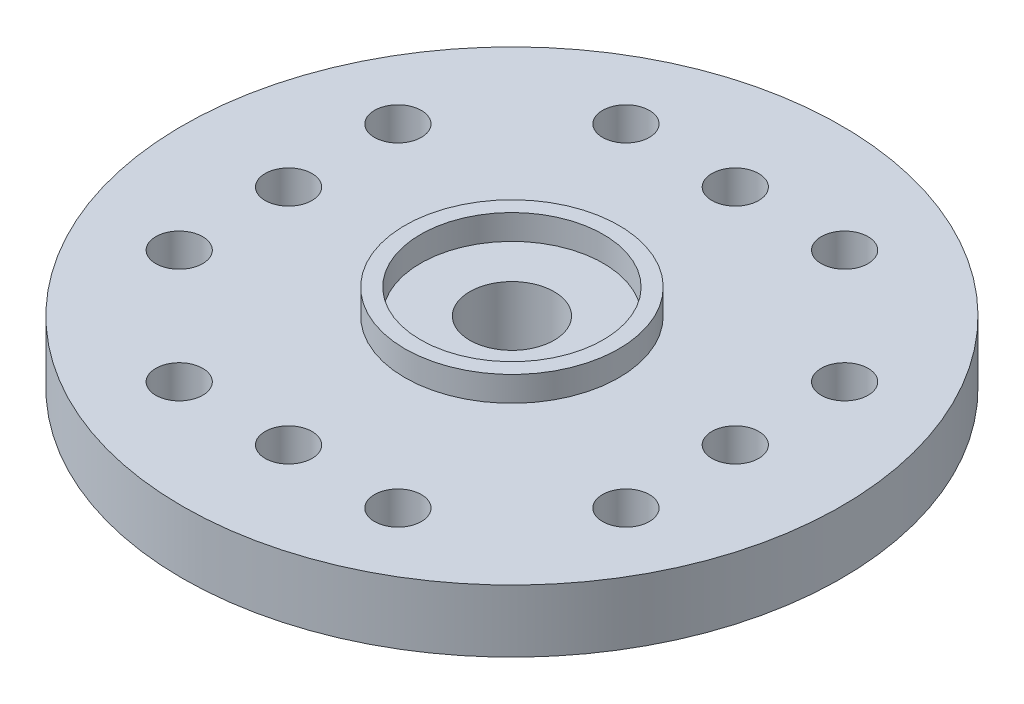
SolidWorks part; units mm, degrees
ref_plane "Front Plane" through (0, 0, 0) normal (0, 0, 1) x (1, 0, 0)
ref_plane "Top Plane" through (0, 0, 0) normal (0, 1, 0) x (1, 0, 0)
ref_plane "Right Plane" through (0, 0, 0) normal (1, 0, 0) x (0, 0, -1)
sketch "Sketch1" plane through (0, 0, 0) normal (0, 1, 0) x (1, 0, 0)
  circle A0 centre (0, 0) radius 4.35
  dimension "D1" = 8.7
extrude "Rebaixo de Encaixe" add sketch "Sketch1" along normal blind 2.6
sketch "Sketch14" plane through (0, 0, 0) normal (0, -1, 0) x (1, 0, 0)
  circle A0 centre (0, 0) radius 2.45
  dimension "D1" = 4.9
extrude "Furo de Encaixe - Servo" cut sketch "Sketch14" against normal blind 3
sketch "Sketch5" plane through (0, 2.6, 0) normal (0, 1, 0) x (1, 0, 0)
  circle A0 centre (0, 0) radius 1.35
  circle A1 centre (0, 0) radius 10.55
  dimension "D1" = 21.1
  dimension "D2" = 2.7
extrude "Base Redonda" add sketch "Sketch5" along normal blind 2
sketch "Sketch8" plane through (0, 4.6, 0) normal (0, 1, 0) x (1, 0, 0)
  circle A0 centre (0, 0) radius 3.425
  circle A1 centre (0, 0) radius 2.925
  dimension "D1" = 6.85
  dimension "D2" = 0.5
extrude "Ressalto" add sketch "Sketch8" along normal blind 0.8
sketch "Sketch9" plane through (0, 4.6, 0) normal (0, 1, 0) x (1, 0, 0)
  line L0 (0, 0) -> (0, 7.15) construction
  line L1 (-7.15, -7.15) -> (7.15, -7.15) construction
  line L2 (-7.15, -7.15) -> (-7.15, 7.15) construction
  line L3 (-7.15, 7.15) -> (7.15, 7.15) construction
  line L4 (7.15, -7.15) -> (7.15, 7.15) construction
  line L5 (-7.15, -7.15) -> (7.15, 7.15) construction
  line L6 (-7.15, 7.15) -> (7.15, -7.15) construction
  circle A0 centre (0, 7.15) radius 0.75
  circle A1 centre (3.5, 7.15) radius 0.75
  circle A2 centre (-3.5, 7.15) radius 0.75
  circle A3 centre (7.15, 3.5) radius 0.75
  circle A4 centre (7.15, 0) radius 0.75
  circle A5 centre (7.15, -3.5) radius 0.75
  circle A6 centre (3.5, -7.15) radius 0.75
  circle A7 centre (0, -7.15) radius 0.75
  circle A8 centre (-3.5, -7.15) radius 0.75
  circle A9 centre (-7.15, -3.5) radius 0.75
  circle A10 centre (-7.15, 0) radius 0.75
  circle A11 centre (-7.15, 3.5) radius 0.75
  point P0 (0, 0)
  point P6 (7.15, 0)
  point P35 (0, 0)
  dimension "D3" = 1.5
  dimension "D4" = 3.5
  dimension "D5" = 3.5
  dimension "D1" = 14.3
  dimension "D2" = 14.3
  dimension "D6" = 4
extrude "Furos de Fixação - Carga Redondo" cut sketch "Sketch9" against normal through all
sketch "Sketch10" [suppressed] plane through (0, 2.6, 0) normal (0, 1, 0) x (1, 0, 0)
  line L0 (0, 0) -> (25.65, 0) construction
  line L1 (26.1003, 3.8236) -> (0.8012, 6.803)
  line L2 (26.1003, -3.8236) -> (0.8012, -6.803)
  arc A0 (0.8012, 6.803) -> (0.8012, -6.803) centre (0, 0) ccw
  circle A1 centre (0, 0) radius 1.35
  arc A3 (26.1003, -3.8236) -> (26.1003, 3.8236) centre (25.65, 0) ccw
  dimension "D1" = 13.7
  dimension "D2" = 32.5
  dimension "D3" = 3.85
  dimension "D4" = 2.7
extrude "Base de 1 Braço" [suppressed] add sketch "Sketch10" along normal blind 4.3
sketch "Sketch11" [suppressed] plane through (0, 6.9, 0) normal (0, 1, 0) x (1, 0, 0)
  circle A0 centre (0, 0) radius 4.25
  dimension "D1" = 8.5
extrude "Rebaixo de Alojamento - 1 Braço" [suppressed] cut sketch "Sketch11" against normal blind 2.1 draft 25
sketch "Sketch12" [suppressed] plane through (0, 0, 0) normal (0, 0, 1) x (1, 0, 0)
  line L0 (29.5, 4.75) -> (11.5, 4.75) construction
  line L1 (29.5, 2.6) -> (29.5, 6.9) construction
  line L2 (11.5, 2.6) -> (11.5, 6.9) construction
  line L3 (0.8012, 2.6) -> (26.1003, 2.6) construction
  line L4 (0.8012, 6.9) -> (26.1003, 6.9) construction
  line L5 (29.5, 2.6) -> (29.5, 3.75)
  line L6 (29.5, 6.9) -> (11.5, 6.9)
  line L7 (29.5, 6.9) -> (29.5, 5.75)
  line L8 (29.5, 5.75) -> (11.5, 5.75)
  line L9 (11.5, 6.9) -> (11.5, 5.75)
  line L10 (29.5, 3.75) -> (11.5, 3.75)
  line L11 (29.5, 2.6) -> (11.5, 2.6)
  line L12 (11.5, 2.6) -> (11.5, 3.75)
  dimension "D1" = 18
  dimension "D2" = 1.15
extrude "Corte do Braço 1" [suppressed] cut sketch "Sketch12" against normal mid plane 13
chamfer "Chanfros 1mm - 1 Braço" [suppressed] distance 1 angle 45
sketch "Sketch15" [suppressed] plane through (0, 5.75, 0) normal (0, 1, 0) x (1, 0, 0)
  line L0 (29.5, 0) -> (11.5, 0) construction
  line L1 (11.5, 5.543) -> (11.5, -5.543) construction
  arc A0 (26.1003, -3.8236) -> (26.1003, 3.8236) centre (25.65, 0) ccw construction
  circle A1 centre (26.15, 0) radius 0.65
  circle A2 centre (23.15, 0) radius 0.65
  circle A3 centre (20.15, 0) radius 0.65
  circle A4 centre (17.15, 0) radius 0.65
  dimension "D1" = 3.35
  dimension "D2" = 1.3
  dimension "D4" = 3
  dimension "D3" = 4
extrude "Furos de Fixação - Carga 1 Braço" [suppressed] cut sketch "Sketch15" against normal through all
sketch "Sketch16" [suppressed] plane through (0, 0, 0) normal (0, -1, 0) x (1, 0, 0)
  circle A0 centre (0, 0) radius 4.35
  dimension "D1" = 8.7
extrude "Fix Altura Rebaixo - 1 Braço" [suppressed] cut sketch "Sketch16" against normal blind 0.8
sketch "Sketch17" [suppressed] plane through (0, 0.8, 0) normal (0, -1, 0) x (1, 0, 0)
  circle A0 centre (0, 0) radius 5
  dimension "D1" = 10
extrude "Fix Diam. Rebaixo - 1 Braço" [suppressed] add sketch "Sketch17" against normal up to next
sketch "Sketch19" [suppressed] plane through (0, 2.6, 0) normal (0, 1, 0) x (1, 0, 0)
  line L0 (23.85, 0) -> (-23.85, 0) construction
  line L1 (0, -6.9) -> (0, 6.9) construction
  line L2 (0.628, 6.8205) -> (24.3335, 3.8195)
  line L3 (-0.628, 6.8205) -> (-24.3335, 3.8195)
  line L4 (-0.628, -6.8205) -> (-24.3335, -3.8195)
  line L5 (0.628, -6.8205) -> (24.3335, -3.8195)
  arc A0 (-0.628, 6.8205) -> (0.628, 6.8205) centre (0, 1.8601) cw
  arc A1 (24.3335, -3.8195) -> (24.3335, 3.8195) centre (23.85, 0) ccw
  arc A2 (-24.3335, 3.8195) -> (-24.3335, -3.8195) centre (-23.85, 0) ccw
  arc A3 (-0.628, -6.8205) -> (0.628, -6.8205) centre (0, -1.8601) ccw
  circle A4 centre (0, 0) radius 1.35
  point P6 (0, 0)
  point P17 (0, 0)
  dimension "D1" = 7.7
  dimension "D4" = 5
  dimension "D5" = 2.7
  dimension "D2" = 13.8
  dimension "D3" = 27.7
extrude "Base 2 Braços" [suppressed] add sketch "Sketch19" along normal blind 4
sketch "Sketch22" [suppressed] plane through (0, 6.6, 0) normal (0, 1, 0) x (1, 0, 0)
  circle A0 centre (0, 0) radius 4.25
  dimension "D1" = 8.5
extrude "Rebaixo de Alojamento - 2 Braços" [suppressed] cut sketch "Sketch22" against normal blind 2 draft 25
sketch "Sketch20" [suppressed] plane through (0, 6.6, 0) normal (0, 1, 0) x (1, 0, 0)
  line L0 (27.7, 0) -> (-27.7, 0) construction
  line L1 (0, 6.8601) -> (0, -6.8601) construction
  arc A0 (24.3335, -3.8195) -> (24.3335, 3.8195) centre (23.85, 0) ccw construction
  arc A1 (-24.3335, 3.8195) -> (-24.3335, -3.8195) centre (-23.85, 0) ccw construction
  arc A2 (0.628, 6.8205) -> (-0.628, 6.8205) centre (0, 1.8601) ccw construction
  arc A3 (-0.628, -6.8205) -> (0.628, -6.8205) centre (0, -1.8601) ccw construction
  circle A4 centre (24.35, 0) radius 0.65
  circle A5 centre (21.35, 0) radius 0.65
  circle A6 centre (18.35, 0) radius 0.65
  circle A7 centre (15.35, 0) radius 0.65
  circle A8 centre (-24.35, 0) radius 0.65
  circle A9 centre (-21.35, 0) radius 0.65
  circle A10 centre (-18.35, 0) radius 0.65
  circle A11 centre (-15.35, 0) radius 0.65
  dimension "D1" = 3.35
  dimension "D2" = 1.3
  dimension "D4" = 3
  dimension "D3" = 4
extrude "Furos de Fixação - Carga 2 Braços" [suppressed] cut sketch "Sketch20" against normal through all
sketch "Sketch21" [suppressed] plane through (0, 0, 0) normal (0, 0, 1) x (1, 0, 0)
  line L0 (0, 6.6) -> (0, 2.6) construction
  line L1 (0.628, 6.6) -> (-0.628, 6.6) construction
  line L2 (-4.35, 2.6) -> (4.35, 2.6) construction
  line L3 (27.7, 4.6) -> (-27.7, 4.6) construction
  line L4 (27.7, 2.6) -> (27.7, 6.6) construction
  line L5 (-27.7, 6.6) -> (-27.7, 2.6) construction
  line L6 (27.7, 2.6) -> (27.7, 3.6)
  line L7 (27.7, 6.6) -> (8.7, 6.6)
  line L8 (27.7, 6.6) -> (27.7, 5.6)
  line L9 (27.7, 5.6) -> (8.7, 5.6)
  line L10 (8.7, 6.6) -> (8.7, 5.6)
  line L11 (27.7, 2.6) -> (8.7, 2.6)
  line L12 (8.7, 2.6) -> (8.7, 3.6)
  line L13 (27.7, 3.6) -> (8.7, 3.6)
  line L14 (-27.7, 3.6) -> (-8.7, 3.6)
  line L15 (-8.7, 2.6) -> (-8.7, 3.6)
  line L16 (-27.7, 2.6) -> (-8.7, 2.6)
  line L17 (-8.7, 6.6) -> (-8.7, 5.6)
  line L18 (-27.7, 5.6) -> (-8.7, 5.6)
  line L19 (-27.7, 6.6) -> (-27.7, 5.6)
  line L20 (-27.7, 6.6) -> (-8.7, 6.6)
  line L21 (-27.7, 2.6) -> (-27.7, 3.6)
  dimension "D1" = 19
  dimension "D2" = 1
extrude "Corte do Braço 2" [suppressed] cut sketch "Sketch21" against normal mid plane 13
chamfer "Chanfros 1mm - 2 Braços" [suppressed] distance 1 angle 45
chamfer "Chanfros 1x3 - 2 Braços Cima" [suppressed] distance 3 distance2 1
chamfer "Chanfros 1x3 - 2 Braços Baixo" [suppressed] distance 1 distance2 3
sketch "Sketch23" [suppressed] plane through (0, 0, 0) normal (0, -1, 0) x (1, 0, 0)
  circle A0 centre (0, 0) radius 4.35
  dimension "D1" = 8.7
extrude "Fix Altura Rebaixo - 2 Braços" [suppressed] cut sketch "Sketch23" against normal blind 0.6
sketch "Sketch24" [suppressed] plane through (0, 0.6, 0) normal (0, -1, 0) x (1, 0, 0)
  circle A0 centre (0, 0) radius 5.15
  dimension "D1" = 10.3
extrude "Fix Diam. Rebaixo - 2 Braços" [suppressed] add sketch "Sketch24" against normal up to next
sketch "Sketch25" [suppressed] plane through (0, 2.6, 0) normal (0, 1, 0) x (1, 0, 0)
  line L5 (0, 0) -> (16.75, 0) construction
  line L6 (5.25, 4.25) -> (7.8067, 4.25)
  line L8 (5.25, -4.25) -> (7.8067, -4.25)
  line L10 (17.2, 2.6622) -> (7.8067, 4.25)
  line L11 (17.2, -2.6622) -> (7.8067, -4.25)
  line L12 (-4.25, -5.25) -> (-4.25, -7.8067)
  line L14 (4.25, -5.25) -> (4.25, -7.8067)
  line L15 (2.6622, -17.2) -> (4.25, -7.8067)
  line L16 (-2.6622, -17.2) -> (-4.25, -7.8067)
  line L17 (0, 0) -> (0, -16.75) construction
  line L18 (-5.25, 4.25) -> (-7.8067, 4.25)
  line L20 (-5.25, -4.25) -> (-7.8067, -4.25)
  line L21 (-17.2, -2.6622) -> (-7.8067, -4.25)
  line L22 (-17.2, 2.6622) -> (-7.8067, 4.25)
  line L23 (0, 0) -> (-16.75, 0) construction
  line L24 (4.25, 5.25) -> (4.25, 7.8067)
  line L26 (-4.25, 5.25) -> (-4.25, 7.8067)
  line L27 (-2.6622, 17.2) -> (-4.25, 7.8067)
  line L28 (2.6622, 17.2) -> (4.25, 7.8067)
  line L29 (0, 0) -> (0, 16.75) construction
  arc A0 (17.2, -2.6622) -> (17.2, 2.6622) centre (16.75, 0) ccw
  arc A1 (-2.6622, -17.2) -> (2.6622, -17.2) centre (0, -16.75) ccw
  arc A2 (-17.2, 2.6622) -> (-17.2, -2.6622) centre (-16.75, 0) ccw
  arc A3 (2.6622, 17.2) -> (-2.6622, 17.2) centre (0, 16.75) ccw
  arc A4 (4.25, 5.25) -> (5.25, 4.25) centre (5.25, 5.25) ccw
  arc A5 (4.25, -5.25) -> (5.25, -4.25) centre (5.25, -5.25) cw
  arc A6 (-4.25, -5.25) -> (-5.25, -4.25) centre (-5.25, -5.25) ccw
  arc A7 (-4.25, 5.25) -> (-5.25, 4.25) centre (-5.25, 5.25) cw
  circle A8 centre (0, 0) radius 1.35
  point P3 (0, 0)
  point P35 (0, 0)
  dimension "D3" = 2.7
  dimension "D2" = 1
  dimension "D7" = 2.7
  dimension "D1" = 8.5
  dimension "D4" = 16.75
  dimension "D6" = 17.2
  dimension "D5" = 4
extrude "Base 4 Braços" [suppressed] add sketch "Sketch25" along normal blind 2.8
sketch "Sketch26" [suppressed] plane through (0, 5.4, 0) normal (0, 1, 0) x (1, 0, 0)
  line L0 (0, 0) -> (19.45, 0) construction
  line L1 (0, 0) -> (0, -19.45) construction
  line L2 (0, 0) -> (-19.45, 0) construction
  line L3 (0, 0) -> (0, 19.45) construction
  arc A0 (17.2, -2.6622) -> (17.2, 2.6622) centre (16.75, 0) ccw construction
  circle A1 centre (16.55, 0) radius 0.75
  circle A2 centre (13.55, 0) radius 0.75
  circle A3 centre (10.55, 0) radius 0.75
  circle A4 centre (7.55, 0) radius 0.75
  circle A5 centre (0, -16.55) radius 0.75
  circle A6 centre (0, -13.55) radius 0.75
  circle A7 centre (0, -10.55) radius 0.75
  circle A8 centre (0, -7.55) radius 0.75
  circle A9 centre (-16.55, 0) radius 0.75
  circle A10 centre (-13.55, 0) radius 0.75
  circle A11 centre (-10.55, 0) radius 0.75
  circle A12 centre (-7.55, 0) radius 0.75
  circle A13 centre (0, 16.55) radius 0.75
  circle A14 centre (0, 13.55) radius 0.75
  circle A15 centre (0, 10.55) radius 0.75
  circle A16 centre (0, 7.55) radius 0.75
  point P44 (0, 0)
  dimension "D1" = 1.5
  dimension "D2" = 4
  dimension "D3" = 3
  dimension "2,15" = 2.15
  dimension "D4" = 4
extrude "Furos de Fixação - Carga 4 Braços" [suppressed] cut sketch "Sketch26" against normal through all
sketch "Sketch27" [suppressed] plane through (0, 5.4, 0) normal (0, 1, 0) x (1, 0, 0)
  circle A0 centre (0, 0) radius 4.25
  circle A1 centre (0, 0) radius 2.9
  circle A2 centre (0, 0) radius 3.4
  circle M43 centre (0, 0) radius 1.35
  dimension "D1" = 8.5
  dimension "D2" = 5.8
  dimension "D3" = 0.5
extrude "Rebaixo Central - 4 Braços" [suppressed] cut sketch "Sketch27" against normal blind 2 contours A0 A2 | A1 M43
sketch "Sketch28" [suppressed] plane through (0, 2.6, 0) normal (0, -1, 0) x (-1, 0, 0)
  line L0 (9.0172, -10.6873) -> (6.8334, -4.8358)
  line L5 (0, 0) -> (13.35, 0) construction
  line L10 (13.7641, 2.4655) -> (7.6047, 3.5)
  line L11 (13.7641, -2.4655) -> (7.6047, -3.5)
  line L12 (4.7469, -13.1528) -> (0.7712, -8.3358)
  line L13 (0, 0) -> (6.675, -11.5614) construction
  line L14 (-4.7469, -13.1528) -> (-0.7712, -8.3358)
  line L15 (-9.0172, -10.6873) -> (-6.8334, -4.8358)
  line L16 (0, 0) -> (-6.675, -11.5614) construction
  line L17 (-13.7641, -2.4655) -> (-7.6047, -3.5)
  line L18 (-13.7641, 2.4655) -> (-7.6047, 3.5)
  line L19 (0, 0) -> (-13.35, 0) construction
  line L20 (-9.0172, 10.6873) -> (-6.8334, 4.8358)
  line L21 (-4.7469, 13.1528) -> (-0.7712, 8.3358)
  line L22 (0, 0) -> (-6.675, 11.5614) construction
  line L23 (4.7469, 13.1528) -> (0.7712, 8.3358)
  line L24 (9.0172, 10.6873) -> (6.8334, 4.8358)
  line L25 (0, 0) -> (6.675, 11.5614) construction
  arc A0 (13.7641, -2.4655) -> (13.7641, 2.4655) centre (13.35, 0) ccw
  circle A9 centre (0, 0) radius 7.5 construction
  arc A10 (4.7469, -13.1528) -> (9.0172, -10.6873) centre (6.675, -11.5614) ccw
  arc A11 (-9.0172, -10.6873) -> (-4.7469, -13.1528) centre (-6.675, -11.5614) ccw
  arc A12 (-13.7641, 2.4655) -> (-13.7641, -2.4655) centre (-13.35, 0) ccw
  arc A13 (-4.7469, 13.1528) -> (-9.0172, 10.6873) centre (-6.675, 11.5614) ccw
  arc A14 (9.0172, 10.6873) -> (4.7469, 13.1528) centre (6.675, 11.5614) ccw
  arc A15 (6.8334, 4.8358) -> (7.6047, 3.5) centre (7.7703, 4.4862) ccw
  arc A16 (7.6047, -3.5) -> (6.8334, -4.8358) centre (7.7703, -4.4862) ccw
  arc A17 (0.7712, -8.3358) -> (-0.7712, -8.3358) centre (0, -8.9724) ccw
  arc A18 (-6.8334, -4.8358) -> (-7.6047, -3.5) centre (-7.7703, -4.4862) ccw
  arc A19 (-7.6047, 3.5) -> (-6.8334, 4.8358) centre (-7.7703, 4.4862) ccw
  arc A20 (-0.7712, 8.3358) -> (0.7712, 8.3358) centre (0, 8.9724) ccw
  circle A21 centre (0, 0) radius 1.35
  point P36 (0, 0)
  dimension "D3" = 2.5
  dimension "D2" = 15
  dimension "D7" = 7
  dimension "D4" = 1
  dimension "D6" = 1
  dimension "D8" = 2.7
  dimension "D1" = 13.35
  dimension "D5" = 6
extrude "Base 6 Braços" [suppressed] add sketch "Sketch28" against normal blind 2.8
sketch "Sketch29" [suppressed] plane through (0, 5.4, 0) normal (0, 1, 0) x (1, 0, 0)
  line L0 (0, 0) -> (15.85, 0) construction
  line L1 (0, 0) -> (7.925, -13.7265) construction
  line L2 (0, 0) -> (-7.925, -13.7265) construction
  line L3 (0, 0) -> (-15.85, 0) construction
  line L4 (0, 0) -> (-7.925, 13.7265) construction
  line L5 (0, 0) -> (7.925, 13.7265) construction
  arc A0 (13.7641, -2.4655) -> (13.7641, 2.4655) centre (13.35, 0) ccw construction
  circle A1 centre (13.7, 0) radius 0.625
  circle A2 centre (10.7, 0) radius 0.625
  circle A3 centre (7.7, 0) radius 0.625
  circle A4 centre (6.85, -11.8645) radius 0.625
  circle A5 centre (5.35, -9.2665) radius 0.625
  circle A6 centre (3.85, -6.6684) radius 0.625
  circle A7 centre (-6.85, -11.8645) radius 0.625
  circle A8 centre (-5.35, -9.2665) radius 0.625
  circle A9 centre (-3.85, -6.6684) radius 0.625
  circle A10 centre (-13.7, 0) radius 0.625
  circle A11 centre (-10.7, 0) radius 0.625
  circle A12 centre (-7.7, 0) radius 0.625
  circle A13 centre (-6.85, 11.8645) radius 0.625
  circle A14 centre (-5.35, 9.2665) radius 0.625
  circle A15 centre (-3.85, 6.6684) radius 0.625
  circle A16 centre (6.85, 11.8645) radius 0.625
  circle A17 centre (5.35, 9.2665) radius 0.625
  circle A18 centre (3.85, 6.6684) radius 0.625
  point P49 (0, 0)
  dimension "D1" = 2.15
  dimension "D2" = 1.25
  dimension "D4" = 3
  dimension "D3" = 3
extrude "Furos de Fixação - Carga 6 Braços" [suppressed] cut sketch "Sketch29" against normal through all
sketch "Sketch30" [suppressed] plane through (0, 5.4, 0) normal (0, 1, 0) x (1, 0, 0)
  circle A0 centre (0, 0) radius 4.25
  circle A1 centre (0, 0) radius 2.9
  circle A2 centre (0, 0) radius 3.4
  circle M21 centre (0, 0) radius 1.35
  dimension "D1" = 8.5
  dimension "D2" = 5.8
  dimension "D3" = 0.5
extrude "Cut-Extrude2" [suppressed] cut sketch "Sketch30" against normal blind 2 contours A1 M21 | A0 A2
sketch "Sketch31" [suppressed] plane through (0, 0, 0) normal (0, -1, 0) x (1, 0, 0)
  line L50 (-1.6931, -1.8394) -> (-1.7174, -2.3677)
  line L51 (-2.2177, -1.9072) -> (-1.6931, -1.8394)
  line L52 (-2.0974, -1.3605) -> (-2.2523, -1.8663)
  line L53 (-2.6223, -1.2958) -> (-2.0974, -1.3605)
  line L54 (-2.3698, -0.7962) -> (-2.6456, -1.2475)
  line L55 (-2.8622, -0.603) -> (-2.3698, -0.7962)
  line L56 (-2.4934, -0.1818) -> (-2.8728, -0.5504)
  line L57 (-2.9222, 0.1278) -> (-2.4934, -0.1818)
  line L58 (-2.4603, 0.444) -> (-2.9194, 0.1813)
  line L59 (-2.7986, 0.8505) -> (-2.4603, 0.444)
  line L60 (-2.2726, 1.0419) -> (-2.7826, 0.9017)
  line L61 (-2.4992, 1.5198) -> (-2.2726, 1.0419)
  line L62 (-1.9421, 1.5743) -> (-2.4709, 1.5653)
  line L63 (-2.0427, 2.0935) -> (-1.9421, 1.5743)
  line L64 (-1.4895, 2.0078) -> (-2.004, 2.1306)
  line L65 (-1.4579, 2.5358) -> (-1.4895, 2.0078)
  line L66 (-0.9434, 2.3152) -> (-1.4112, 2.5621)
  line L67 (-0.7815, 2.8187) -> (-0.9434, 2.3152)
  line L68 (-0.338, 2.477) -> (-0.7297, 2.8325)
  line L69 (-0.056, 2.9245) -> (-0.338, 2.477)
  line L70 (0.2886, 2.4833) -> (-0.0023, 2.925)
  line L71 (0.6731, 2.8465) -> (0.2886, 2.4833)
  line L72 (0.8971, 2.3335) -> (0.7252, 2.8337)
  line L73 (1.3598, 2.5897) -> (0.8971, 2.3335)
  line L74 (1.4492, 2.0371) -> (1.4071, 2.5643)
  line L75 (1.9611, 2.1701) -> (1.4492, 2.0371)
  line L76 (1.9103, 1.6127) -> (2.0006, 2.1338)
  line L77 (2.4392, 1.6142) -> (1.9103, 1.6127)
  line L78 (2.2514, 1.0869) -> (2.4684, 1.5693)
  line L79 (2.764, 0.9569) -> (2.2514, 1.0869)
  line L80 (2.4509, 0.4929) -> (2.7811, 0.9061)
  line L81 (2.9152, 0.2395) -> (2.4509, 0.4929)
  line L82 (2.4965, -0.1321) -> (2.9191, 0.186)
  line L83 (2.8831, -0.493) -> (2.4965, -0.1321)
  line L84 (2.3852, -0.7488) -> (2.8736, -0.5458)
  line L85 (2.67, -1.1946) -> (2.3852, -0.7488)
  line L86 (2.1241, -1.3185) -> (2.6476, -1.2433)
  line L87 (2.289, -1.821) -> (2.1241, -1.3185)
  line L88 (1.7294, -1.8053) -> (2.2552, -1.8627)
  line L89 (1.7642, -2.3331) -> (1.7294, -1.8053)
  line L90 (1.2261, -2.1787) -> (1.7212, -2.365)
  line L91 (1.1286, -2.6985) -> (1.2261, -2.1787)
  line L92 (0.6458, -2.4151) -> (1.0789, -2.7187)
  line L93 (0.422, -2.8944) -> (0.6458, -2.4151)
  line L94 (0.0249, -2.4999) -> (0.3689, -2.9016)
  line L95 (-0.311, -2.9084) -> (0.0249, -2.4999)
  line L96 (-0.5976, -2.4275) -> (-0.3643, -2.9022)
  line L97 (-1.0245, -2.7397) -> (-0.5976, -2.4275)
  line L98 (-1.1825, -2.2027) -> (-1.0746, -2.7205)
  line L99 (-1.6737, -2.3988) -> (-1.1825, -2.2027)
  line L100 (-1.6931, -1.8394) -> (-1.7174, -2.3677)
  line L101 (-2.2177, -1.9072) -> (-1.6931, -1.8394)
  line L102 (-2.0974, -1.3605) -> (-2.2523, -1.8663)
  line L103 (-2.6223, -1.2958) -> (-2.0974, -1.3605)
  line L104 (-2.3698, -0.7962) -> (-2.6456, -1.2475)
  line L105 (-2.8622, -0.603) -> (-2.3698, -0.7962)
  line L106 (-2.4934, -0.1818) -> (-2.8728, -0.5504)
  line L107 (-2.9222, 0.1278) -> (-2.4934, -0.1818)
  line L108 (-2.4603, 0.444) -> (-2.9194, 0.1813)
  line L109 (-2.7986, 0.8505) -> (-2.4603, 0.444)
  line L110 (-2.2726, 1.0419) -> (-2.7826, 0.9017)
  line L111 (-2.4992, 1.5198) -> (-2.2726, 1.0419)
  line L112 (-1.9421, 1.5743) -> (-2.4709, 1.5653)
  line L113 (-2.0427, 2.0935) -> (-1.9421, 1.5743)
  line L114 (-1.4895, 2.0078) -> (-2.004, 2.1306)
  line L115 (-1.4579, 2.5358) -> (-1.4895, 2.0078)
  line L116 (-0.9434, 2.3152) -> (-1.4112, 2.5621)
  line L117 (-0.7815, 2.8187) -> (-0.9434, 2.3152)
  line L118 (-0.338, 2.477) -> (-0.7297, 2.8325)
  line L119 (-0.056, 2.9245) -> (-0.338, 2.477)
  line L120 (0.2886, 2.4833) -> (-0.0023, 2.925)
  line L121 (0.6731, 2.8465) -> (0.2886, 2.4833)
  line L122 (0.8971, 2.3335) -> (0.7252, 2.8337)
  line L123 (1.3598, 2.5897) -> (0.8971, 2.3335)
  line L124 (1.4492, 2.0371) -> (1.4071, 2.5643)
  line L125 (1.9611, 2.1701) -> (1.4492, 2.0371)
  line L126 (1.9103, 1.6127) -> (2.0006, 2.1338)
  line L127 (2.4392, 1.6142) -> (1.9103, 1.6127)
  line L128 (2.2514, 1.0869) -> (2.4684, 1.5693)
  line L129 (2.764, 0.9569) -> (2.2514, 1.0869)
  line L130 (2.4509, 0.4929) -> (2.7811, 0.9061)
  line L131 (2.9152, 0.2395) -> (2.4509, 0.4929)
  line L132 (2.4965, -0.1321) -> (2.9191, 0.186)
  line L133 (2.8831, -0.493) -> (2.4965, -0.1321)
  line L134 (2.3852, -0.7488) -> (2.8736, -0.5458)
  line L135 (2.67, -1.1946) -> (2.3852, -0.7488)
  line L136 (2.1241, -1.3185) -> (2.6476, -1.2433)
  line L137 (2.289, -1.821) -> (2.1241, -1.3185)
  line L138 (1.7294, -1.8053) -> (2.2552, -1.8627)
  line L139 (1.7642, -2.3331) -> (1.7294, -1.8053)
  line L140 (1.2261, -2.1787) -> (1.7212, -2.365)
  line L141 (1.1286, -2.6985) -> (1.2261, -2.1787)
  line L142 (0.6458, -2.4151) -> (1.0789, -2.7187)
  line L143 (0.422, -2.8944) -> (0.6458, -2.4151)
  line L144 (0.0249, -2.4999) -> (0.3689, -2.9016)
  line L145 (-0.311, -2.9084) -> (0.0249, -2.4999)
  line L146 (-0.5976, -2.4275) -> (-0.3643, -2.9022)
  line L147 (-1.0245, -2.7397) -> (-0.5976, -2.4275)
  line L148 (-1.1825, -2.2027) -> (-1.0746, -2.7205)
  line L149 (-1.6737, -2.3988) -> (-1.1825, -2.2027)
  arc A25 (-1.7174, -2.3677) -> (-1.6737, -2.3988) centre (0, 0) ccw
  arc A26 (-2.2523, -1.8663) -> (-2.2177, -1.9072) centre (0, 0) ccw
  arc A27 (-2.6456, -1.2475) -> (-2.6223, -1.2958) centre (0, 0) ccw
  arc A28 (-2.8728, -0.5504) -> (-2.8622, -0.603) centre (0, 0) ccw
  arc A29 (-2.9194, 0.1813) -> (-2.9222, 0.1278) centre (0, 0) ccw
  arc A30 (-2.7826, 0.9017) -> (-2.7986, 0.8505) centre (0, 0) ccw
  arc A31 (-2.4709, 1.5653) -> (-2.4992, 1.5198) centre (0, 0) ccw
  arc A32 (-2.004, 2.1306) -> (-2.0427, 2.0935) centre (0, 0) ccw
  arc A33 (-1.4112, 2.5621) -> (-1.4579, 2.5358) centre (0, 0) ccw
  arc A34 (-0.7297, 2.8325) -> (-0.7815, 2.8187) centre (0, 0) ccw
  arc A35 (-0.0023, 2.925) -> (-0.056, 2.9245) centre (0, 0) ccw
  arc A36 (0.7252, 2.8337) -> (0.6731, 2.8465) centre (0, 0) ccw
  arc A37 (1.4071, 2.5643) -> (1.3598, 2.5897) centre (0, 0) ccw
  arc A38 (2.0006, 2.1338) -> (1.9611, 2.1701) centre (0, 0) ccw
  arc A39 (2.4684, 1.5693) -> (2.4392, 1.6142) centre (0, 0) ccw
  arc A40 (2.7811, 0.9061) -> (2.764, 0.9569) centre (0, 0) ccw
  arc A41 (2.9191, 0.186) -> (2.9152, 0.2395) centre (0, 0) ccw
  arc A42 (2.8736, -0.5458) -> (2.8831, -0.493) centre (0, 0) ccw
  arc A43 (2.6476, -1.2433) -> (2.67, -1.1946) centre (0, 0) ccw
  arc A44 (2.2552, -1.8627) -> (2.289, -1.821) centre (0, 0) ccw
  arc A45 (1.7212, -2.365) -> (1.7642, -2.3331) centre (0, 0) ccw
  arc A46 (1.0789, -2.7187) -> (1.1286, -2.6985) centre (0, 0) ccw
  arc A47 (0.3689, -2.9016) -> (0.422, -2.8944) centre (0, 0) ccw
  arc A48 (-0.3643, -2.9022) -> (-0.311, -2.9084) centre (0, 0) ccw
  arc A49 (-1.0746, -2.7205) -> (-1.0245, -2.7397) centre (0, 0) ccw
  arc A50 (-1.7174, -2.3677) -> (-1.6737, -2.3988) centre (0, 0) ccw
  arc A51 (-2.2523, -1.8663) -> (-2.2177, -1.9072) centre (0, 0) ccw
  arc A52 (-2.6456, -1.2475) -> (-2.6223, -1.2958) centre (0, 0) ccw
  arc A53 (-2.8728, -0.5504) -> (-2.8622, -0.603) centre (0, 0) ccw
  arc A54 (-2.9194, 0.1813) -> (-2.9222, 0.1278) centre (0, 0) ccw
  arc A55 (-2.7826, 0.9017) -> (-2.7986, 0.8505) centre (0, 0) ccw
  arc A56 (-2.4709, 1.5653) -> (-2.4992, 1.5198) centre (0, 0) ccw
  arc A57 (-2.004, 2.1306) -> (-2.0427, 2.0935) centre (0, 0) ccw
  arc A58 (-1.4112, 2.5621) -> (-1.4579, 2.5358) centre (0, 0) ccw
  arc A59 (-0.7297, 2.8325) -> (-0.7815, 2.8187) centre (0, 0) ccw
  arc A60 (-0.0023, 2.925) -> (-0.056, 2.9245) centre (0, 0) ccw
  arc A61 (0.7252, 2.8337) -> (0.6731, 2.8465) centre (0, 0) ccw
  arc A62 (1.4071, 2.5643) -> (1.3598, 2.5897) centre (0, 0) ccw
  arc A63 (2.0006, 2.1338) -> (1.9611, 2.1701) centre (0, 0) ccw
  arc A64 (2.4684, 1.5693) -> (2.4392, 1.6142) centre (0, 0) ccw
  arc A65 (2.7811, 0.9061) -> (2.764, 0.9569) centre (0, 0) ccw
  arc A66 (2.9191, 0.186) -> (2.9152, 0.2395) centre (0, 0) ccw
  arc A67 (2.8736, -0.5458) -> (2.8831, -0.493) centre (0, 0) ccw
  arc A68 (2.6476, -1.2433) -> (2.67, -1.1946) centre (0, 0) ccw
  arc A69 (2.2552, -1.8627) -> (2.289, -1.821) centre (0, 0) ccw
  arc A70 (1.7212, -2.365) -> (1.7642, -2.3331) centre (0, 0) ccw
  arc A71 (1.0789, -2.7187) -> (1.1286, -2.6985) centre (0, 0) ccw
  arc A72 (0.3689, -2.9016) -> (0.422, -2.8944) centre (0, 0) ccw
  arc A73 (-0.3643, -2.9022) -> (-0.311, -2.9084) centre (0, 0) ccw
  arc A74 (-1.0746, -2.7205) -> (-1.0245, -2.7397) centre (0, 0) ccw
  dimension "D1" = 0
extrude "Cut-Extrude3" [suppressed] cut sketch "Sketch31" against normal blind 2.7
